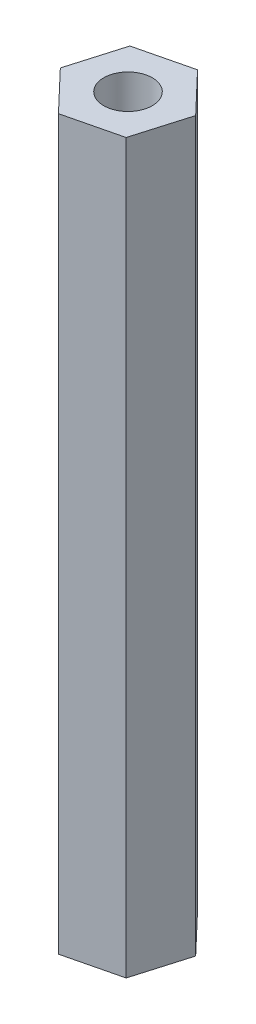
SolidWorks part; units mm, degrees
ref_plane "前视基准面" through (0, 0, 0) normal (0, 0, 1) x (1, 0, 0)
ref_plane "上视基准面" through (0, 0, 0) normal (0, 1, 0) x (1, 0, 0)
ref_plane "右视基准面" through (0, 0, 0) normal (1, 0, 0) x (0, 0, -1)
sketch "草图1" plane through (0, 0, 0) normal (0, 1, 0) x (1, 0, 0)
  line L1 (2.391, -2.5067) -> (3.3663, 0.8173)
  line L2 (3.3663, 0.8173) -> (0.9753, 3.324)
  line L3 (0.9753, 3.324) -> (-2.391, 2.5067)
  line L4 (-2.391, 2.5067) -> (-3.3663, -0.8173)
  line L5 (-3.3663, -0.8173) -> (-0.9753, -3.324)
  line L6 (-0.9753, -3.324) -> (2.391, -2.5067)
  circle A0 centre (0, 0) radius 3 construction
  circle A1 centre (0, 0) radius 1.5
  dimension "D1" = 6
  dimension "D2" = 3
extrude "凸台-拉伸1" add sketch "草图1" along normal blind 45
